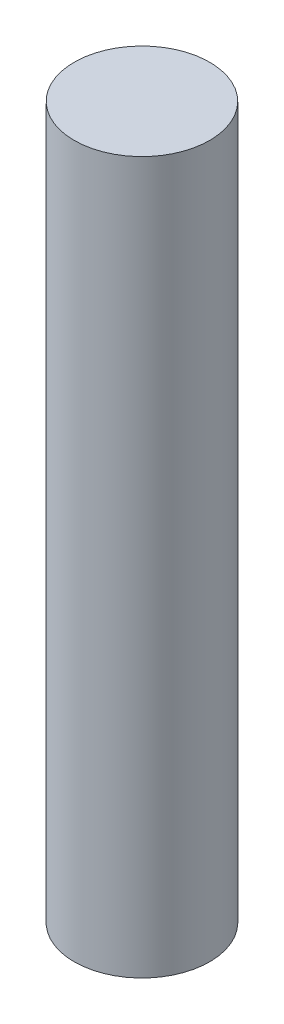
SolidWorks part; units mm, degrees
ref_plane "Front Plane" through (0, 0, 0) normal (0, 0, 1) x (1, 0, 0)
ref_plane "Top Plane" through (0, 0, 0) normal (0, 1, 0) x (1, 0, 0)
ref_plane "Right Plane" through (0, 0, 0) normal (1, 0, 0) x (0, 0, -1)
sketch "Sketch1" plane through (0, 0, 0) normal (0, 1, 0) x (1, 0, 0)
  circle A0 centre (0, 0) radius 2
extrude "Boss-Extrude1" add sketch "Sketch1" against normal blind 13 and the other way blind 8
